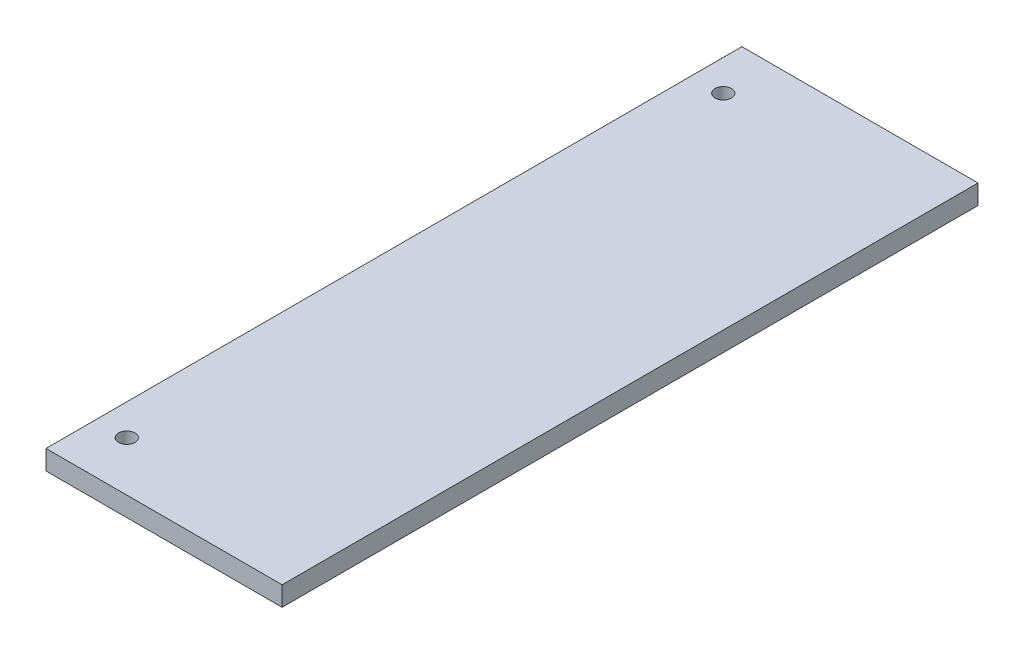
SolidWorks part; units mm, degrees
ref_plane "Front Plane" through (0, 0, 0) normal (0, 0, 1) x (1, 0, 0)
ref_plane "Top Plane" through (0, 0, 0) normal (0, 1, 0) x (1, 0, 0)
ref_plane "Right Plane" through (0, 0, 0) normal (1, 0, 0) x (0, 0, -1)
sketch "Sketch1" plane through (0, 0, 0) normal (0, 1, 0) x (1, 0, 0)
  line L1 (-15.0812, -44.45) -> (15.0813, -44.45)
  line L2 (-15.0812, -44.45) -> (-15.0812, 44.45)
  line L3 (-15.0812, 44.45) -> (15.0813, 44.45)
  line L4 (15.0813, -44.45) -> (15.0813, 44.45)
  line L5 (-15.0812, -44.45) -> (15.0813, 44.45) construction
  line L6 (-15.0812, 44.45) -> (15.0813, -44.45) construction
  point P0 (0, 0)
  dimension "D1" = 30.1625
  dimension "D2" = 88.9
extrude "Boss-Extrude1" add sketch "Sketch1" along normal blind 2.5
sketch "Sketch2" plane through (0, 2.5, 0) normal (0, 1, 0) x (1, 0, 0)
  line L0 (-11.1125, 38.1) -> (-11.1125, -38.1) construction
  circle A0 centre (-11.1125, 38.1) radius 1.05
  circle A1 centre (-11.1125, -38.1) radius 1.05
  point P4 (-8.837, -38.3358)
  point P5 (-11.1125, 0)
  point P7 (-11.1125, -34.6327)
  dimension "D2" = 2.1
  dimension "D1" = 11.1125
  dimension "D3" = 76.2
extrude "Cut-Extrude1" cut sketch "Sketch2" against normal through all
